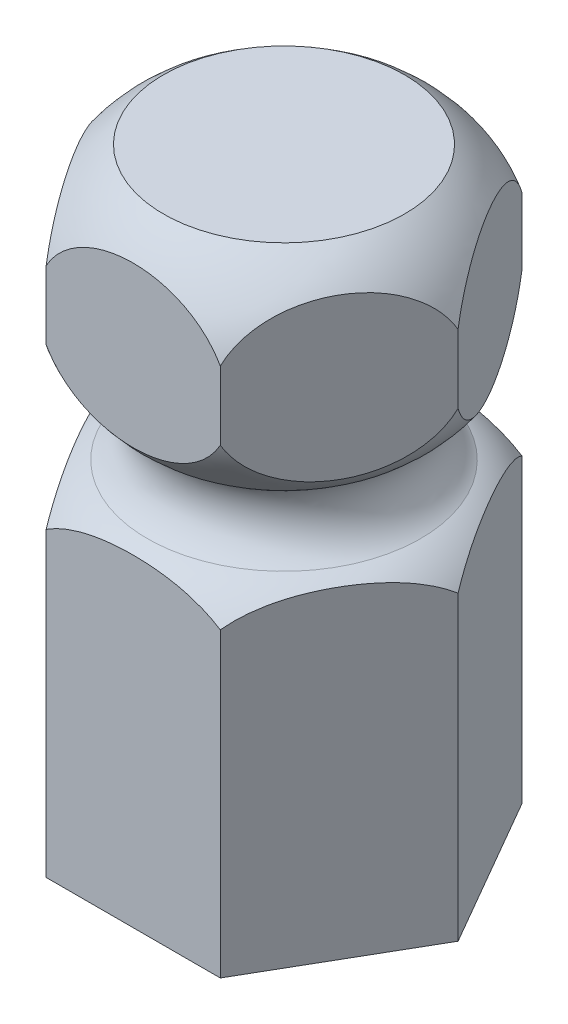
SolidWorks part; units mm, degrees
ref_plane "Front Plane" through (0, 0, 0) normal (0, 0, 1) x (1, 0, 0)
ref_plane "Top Plane" through (0, 0, 0) normal (0, 1, 0) x (1, 0, 0)
ref_plane "Right Plane" through (0, 0, 0) normal (1, 0, 0) x (0, 0, -1)
sketch "Sketch1" plane through (0, 0, 0) normal (0, 1, 0) x (1, 0, 0)
  line L1 (2.8868, 0) -> (1.4434, 2.5)
  line L2 (1.4434, 2.5) -> (-1.4434, 2.5)
  line L3 (-1.4434, 2.5) -> (-2.8868, 0)
  line L4 (-2.8868, 0) -> (-1.4434, -2.5)
  line L5 (-1.4434, -2.5) -> (1.4434, -2.5)
  line L6 (1.4434, -2.5) -> (2.8868, 0)
  circle A0 centre (0, 0) radius 2.5 construction
  dimension "D1" = 5
extrude "Boss-Extrude1" add sketch "Sketch1" along normal blind 10
ref_axis "Axis1" through (0, -0.7951, 0) along (0, 1, 0)
sketch "Sketch3" plane through (0, 0, 0) normal (0, 0, 1) x (1, 0, 0)
  line L0 (-2, 10) -> (-2, 10.9016)
  line L1 (-2.8868, 10) -> (-1.4434, 10) construction
  line L3 (-2.8868, 10) -> (-2.8868, 0) construction
  line L4 (-2, 10.9016) -> (-4.3784, 10.9016)
  line L5 (-4.3784, 10.9016) -> (-4.3784, 5)
  line L6 (-4.3784, 5) -> (-2.8868, 5)
  line L7 (1.4434, 10) -> (-1.4434, 10) construction
  arc A0 (-2, 10) -> (-2, 6.4394) centre (-0.8386, 8.2197) ccw
  arc A1 (-2, 6.4394) -> (-2.2667, 5.4714) centre (-2.6815, 6.1064) cw
  arc A2 (-2.2667, 5.4714) -> (-2.8868, 5) centre (-1.6994, 4.0817) ccw
  point P17 (0, 10)
  dimension "D1" = 5
  dimension "D2" = 2
revolve "Cut-Revolve1" cut sketch "Sketch3" angle 360 about axis through (0, -0.7951, 0) along (0, 1, 0)
